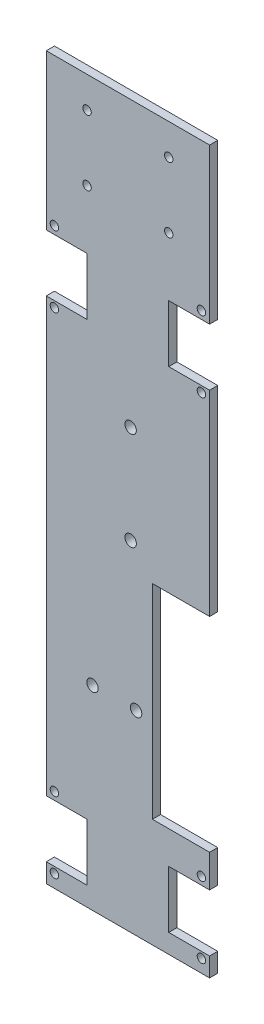
SolidWorks part; units mm, degrees
material "Thornel VCB-20 碳布"
ref_plane "前视基准面" through (0, 0, 0) normal (0, 0, 1) x (1, 0, 0)
ref_plane "上视基准面" through (0, 0, 0) normal (0, 1, 0) x (1, 0, 0)
ref_plane "右视基准面" through (0, 0, 0) normal (1, 0, 0) x (0, 0, -1)
other "Configuration Table"
sketch "草图1" plane through (0, 0, 0) normal (0, 0, 1) x (1, 0, 0)
  line L0 (0, 240) -> (0, 265)
  line L1 (0, 0) -> (60, 0)
  line L2 (0, 0) -> (0, 240)
  line L3 (0, 240) -> (60, 240) construction
  line L4 (60, 0) -> (60, 240)
  line L5 (0, 265) -> (60, 265)
  line L6 (60, 265) -> (60, 240)
  dimension "D1" = 60
  dimension "D2" = 240
  dimension "D3" = 25
extrude "凸台-拉伸1" add sketch "草图1" along normal blind 3
sketch "草图4" plane through (0, 0, 0) normal (0, 0, -1) x (-1, 0, 0)
  line L0 (-60, 7) -> (-45, 7)
  line L1 (-60, 0) -> (-60, 265) construction
  line L2 (-45, 7) -> (-45, 28)
  line L3 (-45, 28) -> (-60, 28)
  line L4 (0, 0) -> (-60, 0) construction
  line L5 (-60, 28) -> (-60, 7)
  line L6 (0, 265) -> (0, 0) construction
  line L7 (0, 28) -> (-15, 28)
  line L8 (0, 28) -> (0, 7)
  line L9 (0, 7) -> (-15, 7)
  line L10 (-15, 28) -> (-15, 7)
  line L11 (-60, 215) -> (0, 215) construction
  line L13 (0, 208) -> (-15, 208)
  line L14 (-15, 208) -> (-15, 187)
  line L15 (-15, 187) -> (0, 187)
  line L16 (-60, 208) -> (-45, 208)
  line L17 (-45, 208) -> (-45, 187)
  line L18 (-45, 187) -> (-60, 187)
  line L19 (-60, 187) -> (-60, 208)
  line L20 (0, 208) -> (0, 187)
  line L21 (-30, 0) -> (-30, 215) construction
  line L25 (-60, 265) -> (0, 265) construction
  dimension "D1" = 7
  dimension "D2" = 21
  dimension "D3" = 15
  dimension "D4" = 50
  dimension "D5" = 21
  dimension "D6" = 7
extrude "切除-拉伸1" cut sketch "草图4" against normal blind 3
sketch "草图5" plane through (0, 0, 0) normal (0, 0, -1) x (-1, 0, 0)
  circle A1 centre (-45, 229.6) radius 1.55
  circle A2 centre (-45, 229.6) radius 1.55
  circle A3 centre (-45, 253.6) radius 1.55
  circle A4 centre (-45, 253.6) radius 1.55
  circle A5 centre (-15, 253.6) radius 1.55
  circle A6 centre (-15, 253.6) radius 1.55
  circle A7 centre (-15, 229.6) radius 1.55
  circle A8 centre (-15, 229.6) radius 1.55
  circle A9 centre (-57, 184.75) radius 1.55
  circle A10 centre (-57, 184.75) radius 1.55
  circle A11 centre (-3, 184.75) radius 1.55
  circle A12 centre (-3, 184.75) radius 1.55
  circle A13 centre (-3, 210.85) radius 1.55
  circle A14 centre (-3, 210.85) radius 1.55
  circle A15 centre (-57, 210.85) radius 1.55
  circle A16 centre (-57, 210.85) radius 1.55
  circle A17 centre (-13, 127.7) radius 1.55
  circle A18 centre (-13, 127.7) radius 1.55 construction
  circle A19 centre (-37, 127.7) radius 1.55
  circle A20 centre (-37, 127.7) radius 1.55 construction
  circle A21 centre (-37, 157.7) radius 1.55
  circle A22 centre (-37, 157.7) radius 1.55 construction
  circle A23 centre (-13, 157.7) radius 1.55
  circle A24 centre (-13, 157.7) radius 1.55 construction
  circle A25 centre (-57, 4.75) radius 1.55
  circle A26 centre (-57, 4.75) radius 1.55
  circle A27 centre (-3, 4.75) radius 1.55
  circle A28 centre (-3, 4.75) radius 1.55
  circle A29 centre (-3, 30.85) radius 1.55
  circle A30 centre (-3, 30.85) radius 1.55
  circle A31 centre (-57, 30.85) radius 1.55
  circle A32 centre (-57, 30.85) radius 1.55
  dimension "D1" = 0
  dimension "D2" = 0
  dimension "D3" = 0
  dimension "D4" = 0
  dimension "D5" = 0
  dimension "D6" = 0
  dimension "D7" = 0
  dimension "D8" = 0
  dimension "D9" = 0
  dimension "D10" = 0
  dimension "D11" = 0
  dimension "D12" = 0
  dimension "D13" = 0
  dimension "D14" = 0
  dimension "D15" = 0
  dimension "D16" = 0
extrude "切除-拉伸2" cut sketch "草图5" against normal through all
sketch "草图7" plane through (0, 0, 0) normal (0, 0, -1) x (-1, 0, 0)
  line L0 (-60, 40) -> (-39, 40)
  line L1 (-60, 28) -> (-60, 187) construction
  line L2 (-39, 40) -> (-39, 115)
  line L3 (-39, 115) -> (-60, 115)
  line L4 (0, 0) -> (-60, 0) construction
  line L5 (-60, 40) -> (-60, 115)
  dimension "D1" = 40
  dimension "D2" = 115
  dimension "D3" = 21
extrude "切除-拉伸3" cut sketch "草图7" against normal through all
sketch "草图8" plane through (0, 0, 3) normal (0, 0, 1) x (1, 0, 0)
  circle A0 centre (31, 160.7) radius 2.1 construction
  circle A1 centre (31, 124.7) radius 2.1 construction
  circle A2 centre (31, 160.7) radius 2.1
  circle A3 centre (31, 124.7) radius 2.1
extrude "切除-拉伸4" cut sketch "草图8" against normal through all
sketch "草图9" plane through (0, 0, 0) normal (0, 0, -1) x (-1, 0, 0)
  circle A0 centre (-17, 71.6) radius 2.1 construction
  circle A1 centre (-33, 71.6) radius 2.1 construction
  circle A2 centre (-17, 71.6) radius 2.1
  circle A3 centre (-33, 71.6) radius 2.1
extrude "切除-拉伸5" cut sketch "草图9" against normal through all
